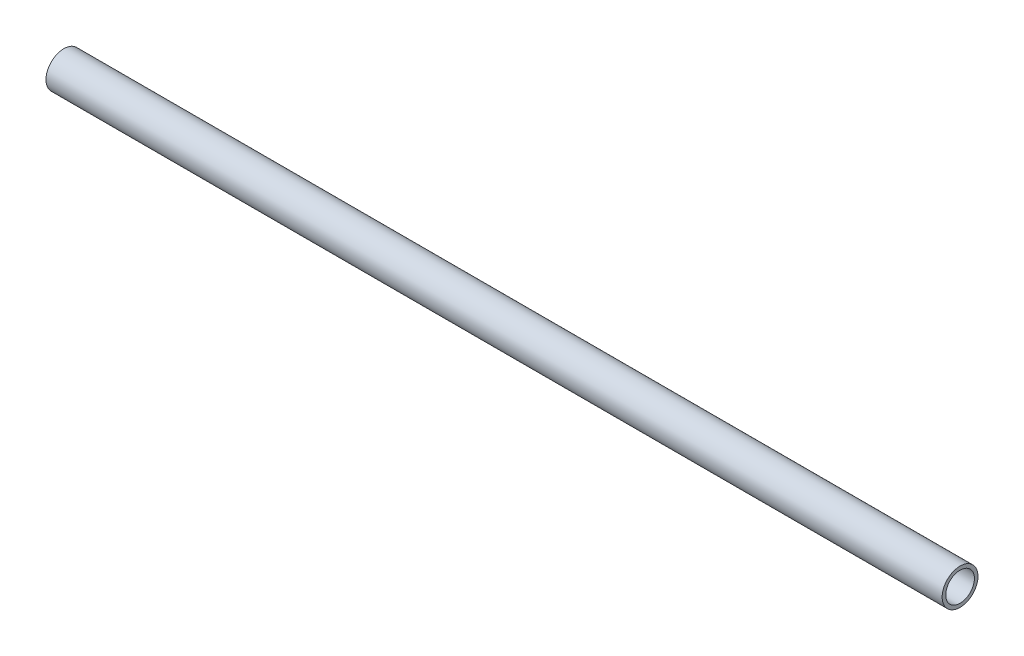
SolidWorks part; units mm, degrees
ref_plane "Front Plane" through (0, 0, 0) normal (0, 0, 1) x (1, 0, 0)
ref_plane "Top Plane" through (0, 0, 0) normal (0, 1, 0) x (1, 0, 0)
ref_plane "Right Plane" through (0, 0, 0) normal (1, 0, 0) x (0, 0, -1)
sketch "Sketch1" plane through (0, 0, 0) normal (1, 0, 0) x (0, 0, -1)
  circle A0 centre (0, 0) radius 5
  circle A1 centre (0, 0) radius 4
  dimension "D1" = 10
  dimension "D2" = 8
extrude "Boss-Extrude1" add sketch "Sketch1" along normal blind 250
